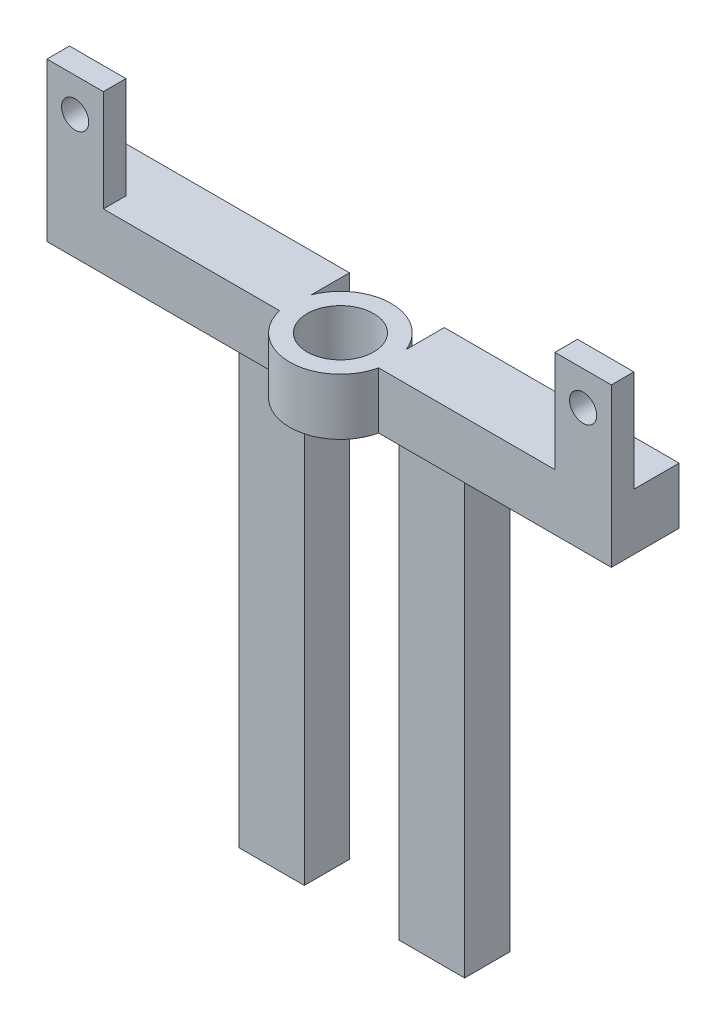
SolidWorks part; units mm, degrees
ref_plane "Front Plane" through (0, 0, 0) normal (0, 0, 1) x (1, 0, 0)
ref_plane "Top Plane" through (0, 0, 0) normal (0, 1, 0) x (1, 0, 0)
ref_plane "Right Plane" through (0, 0, 0) normal (1, 0, 0) x (0, 0, -1)
sketch "Sketch2" plane through (0, 0, -26.5) normal (0, 0, 1) x (1, 0, 0)
  line L0 (-25, -17.75) -> (-20, -17.75)
  line L1 (-25, -22.75) -> (-25, -7.1414) construction
  line L2 (-20, -25.75) -> (-20, -5.75) construction
  line L3 (-20, -17.75) -> (-20, -26.75)
  line L4 (-22.5, -20.75) -> (22.5, -20.75) construction
  line L5 (0, -20.75) -> (0, -47.9164) construction
  line L6 (-20, -26.75) -> (20, -26.75)
  line L7 (-25, -17.75) -> (-25, -31.75)
  line L8 (-25, -78.5) -> (-25, -30.75) construction
  line L9 (-25, -31.75) -> (25, -31.75)
  line L10 (25, -17.75) -> (20, -17.75)
  line L11 (20, -17.75) -> (20, -26.75)
  line L12 (25, -17.75) -> (25, -31.75)
  circle A0 centre (22.5, -20.75) radius 1.2 construction
  circle A1 centre (-22.5, -20.75) radius 1.2 construction
  circle A2 centre (22.5, -20.75) radius 1.2
  circle A3 centre (-22.5, -20.75) radius 1.2
  point P17 (0, -26.75)
  point P25 (0, -31.75)
  dimension "D2" = 3
  dimension "D1" = 5
  dimension "D3" = 6
extrude "Boss-Extrude1" add sketch "Sketch2" along normal blind 2 from surface at 26.5
sketch "Sketch3" plane through (0, 0, 0) normal (0, 1, 0) x (1, 0, 0)
  circle A0 centre (0, -1) radius 4.5
  dimension "D1" = 9
extrude "Boss-Extrude2" add sketch "Sketch3" against normal up to surface (5 mm away) from surface at -26.75 up to face at (0, -31.75, 1) starting at face at (0, -26.75, 1)
sketch "Sketch4" plane through (0, 0, 0) normal (0, 1, 0) x (1, 0, 0)
  circle A0 centre (0, -1) radius 2.95
  dimension "D1" = 5.9
extrude "Cut-Extrude1" cut sketch "Sketch4" against normal through all both and the other way through all
sketch "Sketch5" plane through (0, 0, 0) normal (0, 0, 1) x (1, 0, 0)
  line L0 (-25, -31.75) -> (-10, -31.75)
  line L1 (-4.3875, -31.75) -> (-25, -31.75) construction
  line L2 (-10, -31.75) -> (-10, -26.75)
  line L3 (-20, -26.75) -> (-4.3875, -26.75) construction
  line L4 (-10, -26.75) -> (-25, -26.75)
  line L5 (-25, -31.75) -> (-25, -17.75) construction
  line L6 (-25, -26.75) -> (-25, -31.75)
  line L7 (0, -26.75) -> (0, -31.75) construction
  line L8 (4.3875, -26.75) -> (-4.3875, -26.75) construction
  line L9 (-4.3875, -31.75) -> (4.3875, -31.75) construction
  line L10 (25, -26.75) -> (25, -31.75)
  line L11 (10, -26.75) -> (25, -26.75)
  line L12 (10, -31.75) -> (10, -26.75)
  line L13 (25, -31.75) -> (10, -31.75)
  dimension "D1" = 15
extrude "Boss-Extrude3" add sketch "Sketch5" along normal up to surface (4 mm away) from surface contours L13 L10 L11 L12 | L6 L0 L2 L4
sketch "Sketch6" plane through (0, 0, 0) normal (0, 1, 0) x (1, 0, 0)
  line L0 (4.3875, 0) -> (10, 0) construction
  line L1 (10, 4) -> (4.2, 4)
  line L2 (10, 4) -> (10, 0)
  line L3 (10, 0) -> (4.2, 0)
  line L4 (4.2, 4) -> (4.2, 0)
  line L5 (0, 3.5) -> (0, 9.8099) construction
  line L6 (-4.2, 4) -> (-4.2, 0)
  line L7 (-10, 0) -> (-4.2, 0)
  line L8 (-10, 4) -> (-10, 0)
  line L9 (-10, 4) -> (-4.2, 4)
  arc A0 (4.3875, 0) -> (-4.3875, 0) centre (0, -1) ccw construction
  dimension "D1" = 5.8
extrude "Boss-Extrude6" add sketch "Sketch6" against normal blind 45 from surface at -26.75 starting at face at (-2.95, -26.75, 1)
